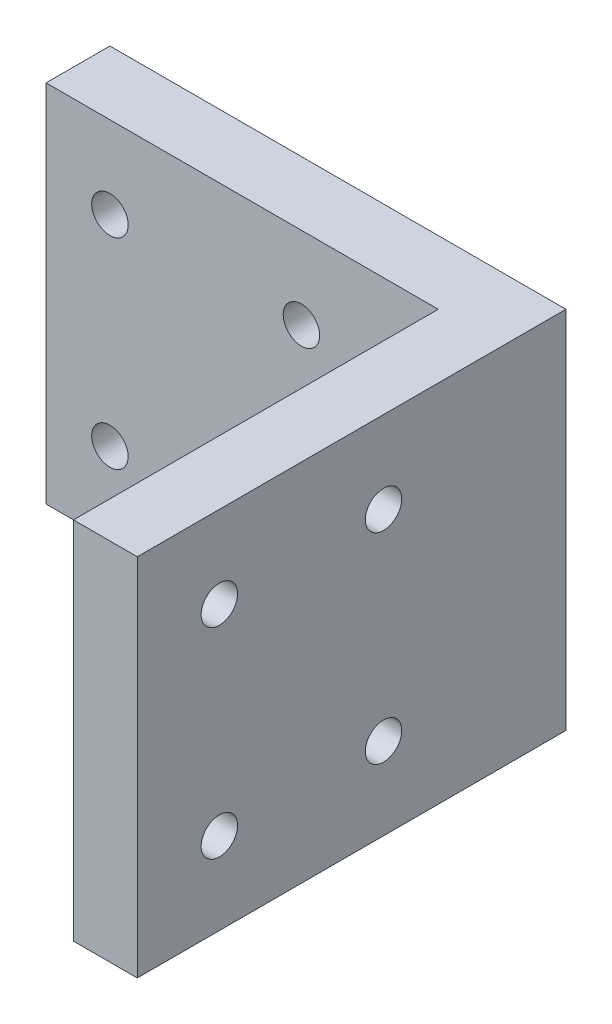
SolidWorks part; units mm, degrees
ref_plane "Front Plane" through (0, 0, 0) normal (0, 0, 1) x (1, 0, 0)
ref_plane "Top Plane" through (0, 0, 0) normal (0, 1, 0) x (1, 0, 0)
ref_plane "Right Plane" through (0, 0, 0) normal (1, 0, 0) x (0, 0, -1)
sketch "Sketch1" plane through (0, 0, 0) normal (0, 0, 1) x (1, 0, 0)
  line L1 (-45.2174, 8.913) -> (4.7826, 8.913)
  line L2 (-45.2174, 8.913) -> (-45.2174, -31.087)
  line L3 (-45.2174, -31.087) -> (4.7826, -31.087)
  line L4 (4.7826, 8.913) -> (4.7826, -31.087)
  dimension "D1" = 40
  dimension "D2" = 50
extrude "Boss-Extrude1" add sketch "Sketch1" along normal blind 7
sketch "Sketch2" plane through (0, 0, 7) normal (0, 0, 1) x (1, 0, 0)
  line L0 (4.7826, 8.913) -> (-45.2174, 8.913) construction
  line L1 (-2.2174, 8.913) -> (4.7826, 8.913)
  line L2 (-2.2174, 8.913) -> (-2.2174, -31.087)
  line L3 (-2.2174, -31.087) -> (4.7826, -31.087)
  line L4 (4.7826, 8.913) -> (4.7826, -31.087)
  dimension "D1" = 7
extrude "Boss-Extrude2" add sketch "Sketch2" along normal blind 40
sketch "Sketch3" plane through (0, 0, 7) normal (0, 0, 1) x (1, 0, 0)
  line L0 (-45.2174, 8.913) -> (-45.2174, -31.087) construction
  line L1 (-2.2174, 8.913) -> (-45.2174, 8.913) construction
  line L2 (-45.2174, -31.087) -> (-2.2174, -31.087) construction
  line L3 (-2.2174, 8.913) -> (-2.2174, -31.087) construction
  circle A0 centre (-38.2174, -0.087) radius 2
  circle A1 centre (-38.2174, -22.087) radius 2
  circle A2 centre (-17.2174, -0.087) radius 2
  circle A3 centre (-17.2174, -22.087) radius 2
  dimension "D1" = 4
  dimension "D2" = 4
  dimension "D3" = 7
  dimension "D4" = 0
  dimension "D5" = 9
  dimension "D6" = 9
  dimension "D7" = 0
  dimension "D8" = 0
  dimension "D9" = 15
  dimension "D10" = 0
  dimension "D11" = 4
  dimension "D12" = 4
extrude "Cut-Extrude1" cut sketch "Sketch3" against normal blind 40
sketch "Sketch4" plane through (-2.2174, 0, 0) normal (-1, 0, 0) x (0, 0, 1)
  line L0 (47, 8.913) -> (7, 8.913) construction
  line L1 (47, -31.087) -> (7, -31.087) construction
  line L2 (47, 8.913) -> (47, -31.087) construction
  line L3 (7, 8.913) -> (7, -31.087) construction
  circle A0 centre (38, -0.087) radius 2
  circle A1 centre (38, -22.087) radius 2
  circle A2 centre (20, -0.087) radius 2
  circle A3 centre (20, -22.087) radius 2
  dimension "D1" = 4
  dimension "D2" = 4
  dimension "D3" = 4
  dimension "D4" = 4
  dimension "D5" = 0
  dimension "D6" = 0
  dimension "D7" = 9
  dimension "D8" = 9
  dimension "D9" = 0
  dimension "D10" = 0
  dimension "D11" = 9
  dimension "D12" = 13
extrude "Cut-Extrude2" cut sketch "Sketch4" against normal blind 40
